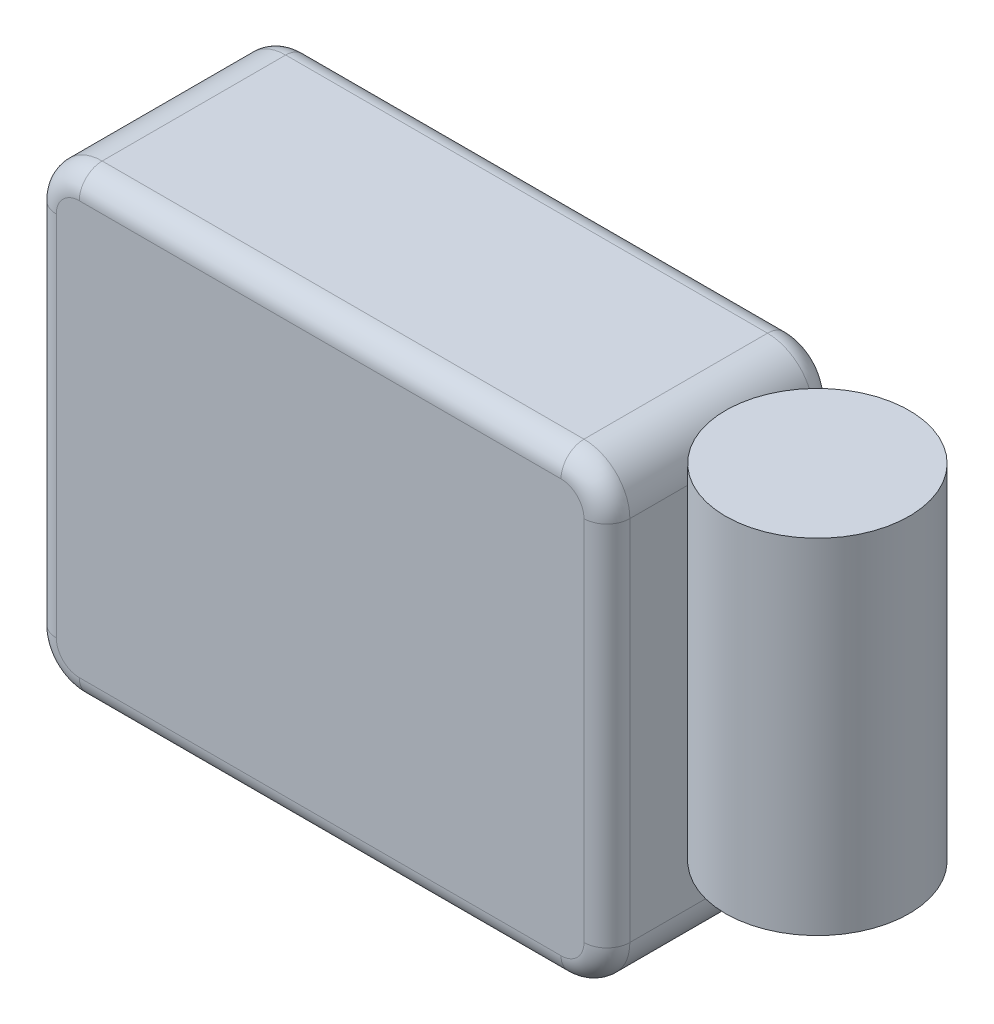
SolidWorks part; units mm, degrees
ref_plane "Front Plane" through (0, 0, 0) normal (0, 0, 1) x (1, 0, 0)
ref_plane "Top Plane" through (0, 0, 0) normal (0, 1, 0) x (1, 0, 0)
ref_plane "Right Plane" through (0, 0, 0) normal (1, 0, 0) x (0, 0, -1)
sketch "Sketch1" plane through (0, 0, 0) normal (0, 0, 1) x (1, 0, 0)
  line L1 (126.1489, 23.0571) -> (151.1489, 23.0571)
  line L2 (126.1489, 23.0571) -> (126.1489, 3.0571)
  line L3 (126.1489, 3.0571) -> (151.1489, 3.0571)
  line L4 (151.1489, 23.0571) -> (151.1489, 3.0571)
extrude "Boss-Extrude1" add sketch "Sketch1" along normal blind 10
sketch "Sketch2" plane through (0, 23.0571, 0) normal (0, 1, 0) x (1, 0, 0)
  line L1 (151.1489, -10) -> (151.1489, 0) construction
  circle A0 centre (155.1489, -4.8262) radius 4
  dimension "D1" = 4
extrude "Boss-Extrude2" add sketch "Sketch2" against normal blind 15 separate body
fillet "Fillet1" radius 2 4 edges at (126.1489, 23.0571, 5) (151.1489, 23.0571, 5) (151.1489, 3.0571, 5) (126.1489, 3.0571, 5)
fillet "Fillet2" radius 1 16 edges at (126.7347, 3.6429, 0) (138.6489, 3.0571, 0) (150.5631, 3.6429, 0) (151.1489, 13.0571, 0) (150.5631, 22.4713, 0) (138.6489, 23.0571, 0) (126.7347, 22.4713, 0) (126.1489, 13.0571, 0) (150.5631, 22.4713, 10) (151.1489, 13.0571, 10) (150.5631, 3.6429, 10) (138.6489, 3.0571, 10) (126.7347, 3.6429, 10) (126.1489, 13.0571, 10) (126.7347, 22.4713, 10) (138.6489, 23.0571, 10)
